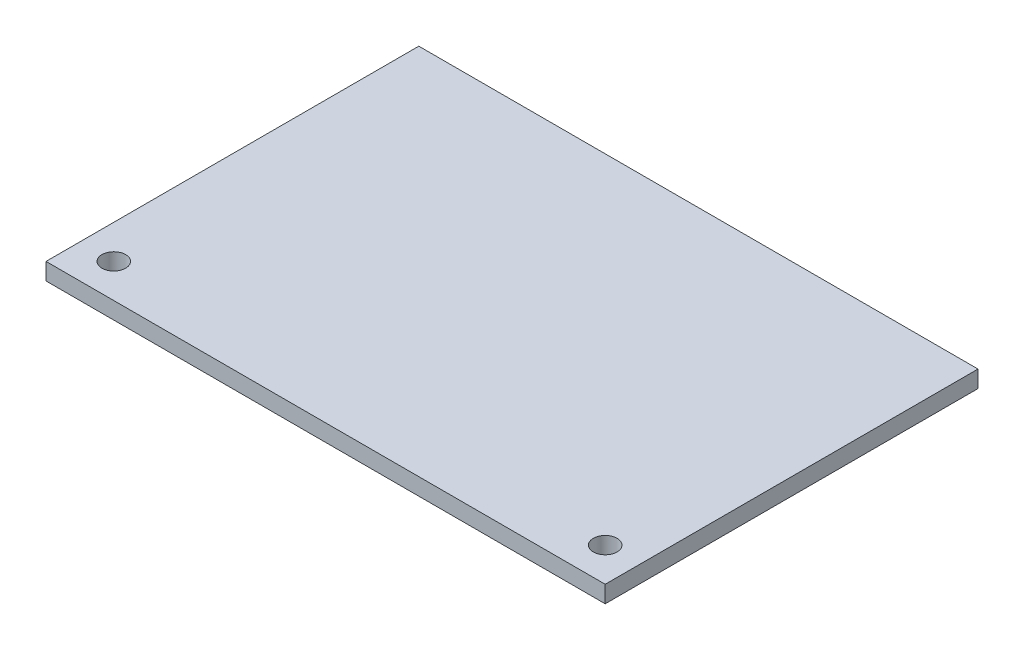
SolidWorks part; units mm, degrees
ref_plane "Front Plane" through (0, 0, 0) normal (0, 0, 1) x (1, 0, 0)
ref_plane "Top Plane" through (0, 0, 0) normal (0, 1, 0) x (1, 0, 0)
ref_plane "Right Plane" through (0, 0, 0) normal (1, 0, 0) x (0, 0, -1)
sketch "Sketch1" plane through (0, 0, 0) normal (0, 1, 0) x (1, 0, 0)
  line L1 (-82.5, 55) -> (82.5, 55)
  line L2 (-82.5, 55) -> (-82.5, -55)
  line L3 (-82.5, -55) -> (82.5, -55)
  line L4 (82.5, 55) -> (82.5, -55)
  line L5 (-82.5, 55) -> (82.5, -55) construction
  line L6 (-82.5, -55) -> (82.5, 55) construction
  circle A0 centre (72.5, -45) radius 3.5
  circle A1 centre (-72.5, -45) radius 3.5
  point P0 (0, 0)
  dimension "D3" = 7
  dimension "D1" = 110
  dimension "D2" = 165
  dimension "D4" = 10
  dimension "D5" = 10
  dimension "D6" = 10
extrude "Boss-Extrude1" add sketch "Sketch1" along normal blind 5
